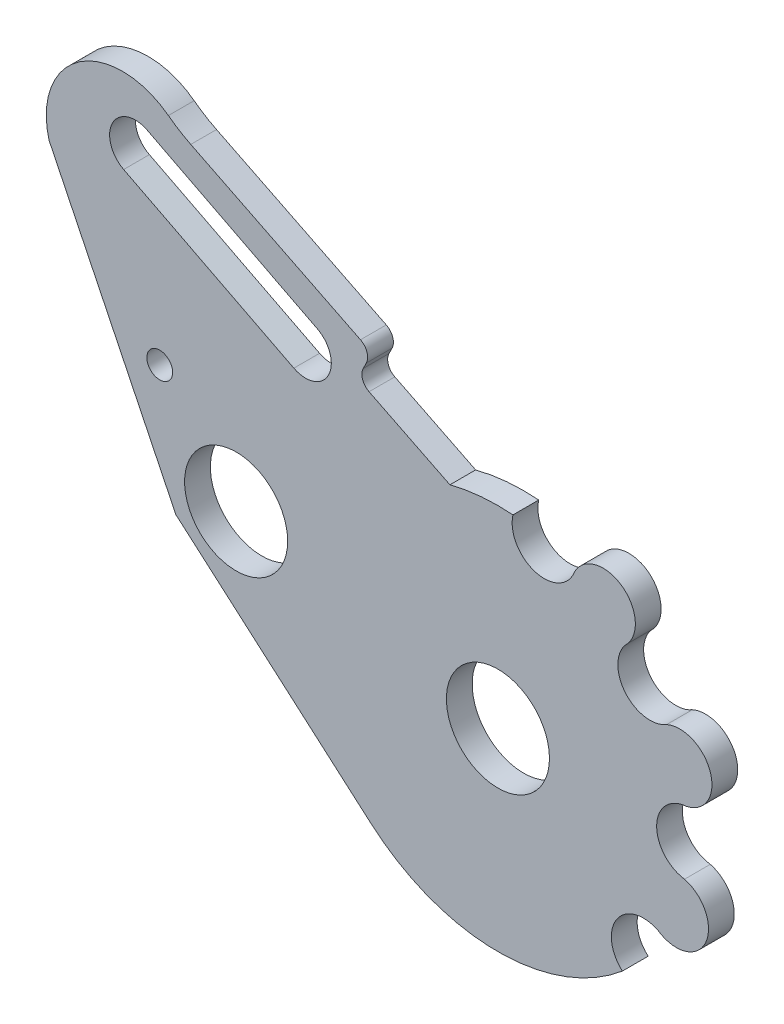
SolidWorks part; units mm, degrees
ref_plane "Plan de face" through (0, 0, 0) normal (0, 0, 1) x (1, 0, 0)
ref_plane "Plan de dessus" through (0, 0, 0) normal (0, 1, 0) x (1, 0, 0)
ref_plane "Plan de droite" through (0, 0, 0) normal (1, 0, 0) x (0, 0, -1)
sketch "Esquisse1" plane through (0, 0, 0) normal (0, 0, 1) x (1, 0, 0)
  line L0 (-10.9021, 18.0926) -> (-3.7284, 14.5292)
  line L1 (-10.9021, 18.0926) -> (-9.7741, 20.3635)
  line L2 (-9.7741, 20.3635) -> (-25.0053, 27.9292)
  line L3 (-34.8561, 22.147) -> (-25.0053, 1.8844)
  line L4 (-25.0053, 1.8844) -> (-2.2341, -17.9446)
  line L5 (-28.148, 24.8441) -> (-14.936, 18.0926) construction
  line L6 (-27.2379, 26.625) -> (-14.0259, 19.8736)
  line L7 (-29.0581, 23.0631) -> (-15.846, 16.3117)
  circle A1 centre (3.6018, 14.3836) radius 2.5
  circle A2 centre (0, 0) radius 15 construction
  circle A3 centre (8.1697, 12.374) radius 2.5
  circle A4 centre (0, 0) radius 15
  circle A5 centre (11.8121, 8.9629) radius 2.5
  circle A6 centre (0, 0) radius 15
  circle A7 centre (14.1167, 4.5365) radius 2.5
  circle A8 centre (0, 0) radius 15
  circle A9 centre (14.8222, -0.4037) radius 2.5
  circle A10 centre (0, 0) radius 15
  circle A11 centre (13.8488, -5.2982) radius 2.5
  circle A12 centre (0, 0) radius 15
  circle A13 centre (11.3068, -9.5925) radius 2.5
  circle A14 centre (0, 0) radius 15
  arc A15 (-25.0053, 27.9292) -> (-34.8561, 22.147) centre (-29.1494, 23.7071) ccw
  circle A16 centre (0, 0) radius 4
  arc A17 (-27.2379, 26.625) -> (-29.0581, 23.0631) centre (-28.148, 24.8441) ccw
  arc A23 (-15.846, 16.3117) -> (-14.0259, 19.8736) centre (-14.936, 18.0926) ccw
  circle A24 centre (-20.3252, 4.4391) radius 4
  circle A25 centre (-26.2564, 11.3193) radius 1
  point P27 (0, 0)
  point P34 (-21.542, 21.4683)
  point P38 (0, 0)
  point P49 (0, 0)
  dimension "D1" = 2
  dimension "D3" = 5
  dimension "D6" = 8
  dimension "D7" = 8
  dimension "D9" = 5
  dimension "D8" = 2
  dimension "D10" = 3
  dimension "D4" = 7
extrude "Boss.-Extru.1" add sketch "Esquisse1" along normal blind 2
fillet "Congé1" radius 1 2 edges at (-10.9021, 18.0926, 1) (-9.7741, 20.3635, 1)
fillet "Congé2" radius 11 1 edges at (-25.0053, 27.9292, 1)
